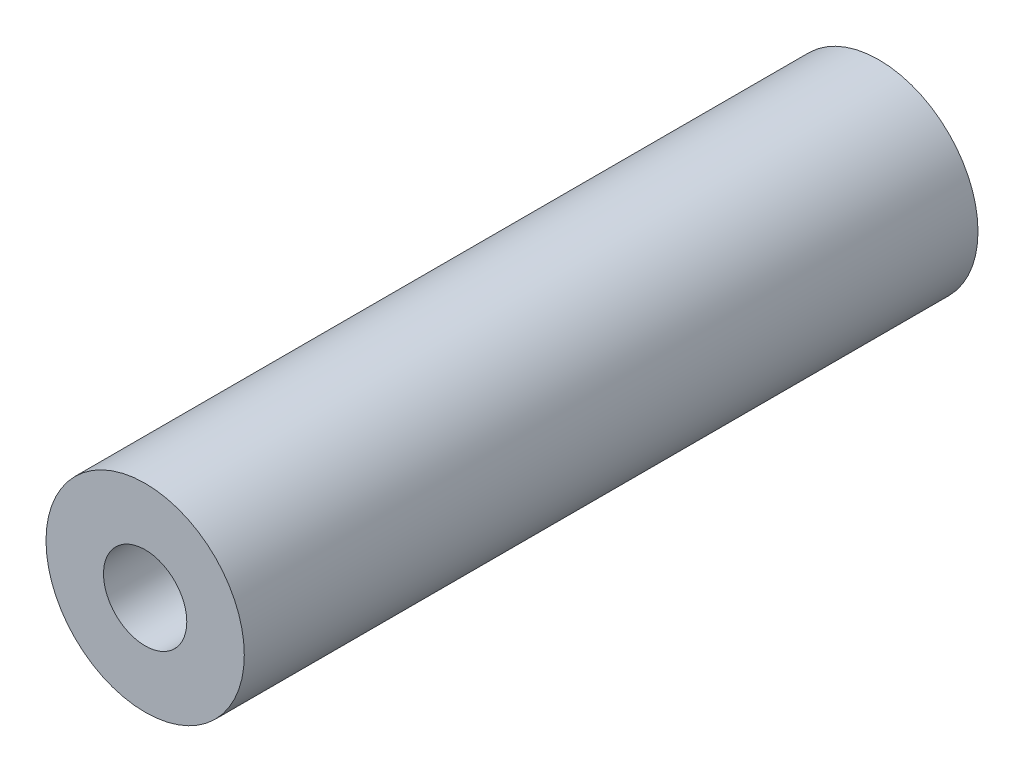
SolidWorks part; units mm, degrees
material "SKD11淬火HRC56-60"
ref_plane "前基準面" through (0, 0, 0) normal (0, 0, 1) x (1, 0, 0)
ref_plane "上基準面" through (0, 0, 0) normal (0, 1, 0) x (1, 0, 0)
ref_plane "右基準面" through (0, 0, 0) normal (1, 0, 0) x (0, 0, -1)
sketch "草图1" plane through (0, 0, 0) normal (0, 0, 1) x (1, 0, 0)
  circle A0 centre (0, 0) radius 5
  dimension "D1" = 10
extrude "凸台-拉伸1" add sketch "草图1" along normal blind 37
hole_wizard "M5 螺纹孔1" positions "草图3" profile "草图2" tap size "M5" standard "ISO"
sketch "草图3" plane through (0, 0, 37) normal (0, 0, 1) x (1, 0, 0)
  point P0 (0, 0)
sketch "草图2" plane through (0, 0, 37) normal (1, 0, 0) x (0, -1, 0)
  line L0 (0, 0) -> (0, 13.6618)
  line L1 (0, 13.6618) -> (2.1, 12.4)
  line L2 (2.1, 12.4) -> (2.1, 0)
  line L5 (2.1, 0) -> (0, 0)
  line L10 (0, 13.6618) -> (-2.1, 12.4) construction
  line L11 (0, -6.35) -> (0, 107.95) construction
  dimension "螺纹孔钻头直径" = 4.2
  dimension "螺纹孔钻头深度" = 12.4
  dimension "导头角度" = 118
cosmetic thread "孔螺蚊线1" parameters "D1"=10, "D2"=5
hole_wizard "M5 螺纹孔2" positions "草图6" profile "草图5" tap size "M5" standard "ISO"
sketch "草图6" plane through (0, 0, 0) normal (0, 0, -1) x (-1, 0, 0)
  point P0 (0, 0)
sketch "草图5" plane through (0, 0, 0) normal (1, 0, 0) x (0, 1, 0)
  line L0 (0, 0) -> (0, 13.6618)
  line L1 (0, 13.6618) -> (2.1, 12.4)
  line L2 (2.1, 12.4) -> (2.1, 0)
  line L5 (2.1, 0) -> (0, 0)
  line L10 (0, 13.6618) -> (-2.1, 12.4) construction
  line L11 (0, -6.35) -> (0, 107.95) construction
  dimension "螺纹孔钻头直径" = 4.2
  dimension "螺纹孔钻头深度" = 12.4
  dimension "导头角度" = 118
cosmetic thread "孔螺蚊线2" parameters "D1"=10, "D2"=5
